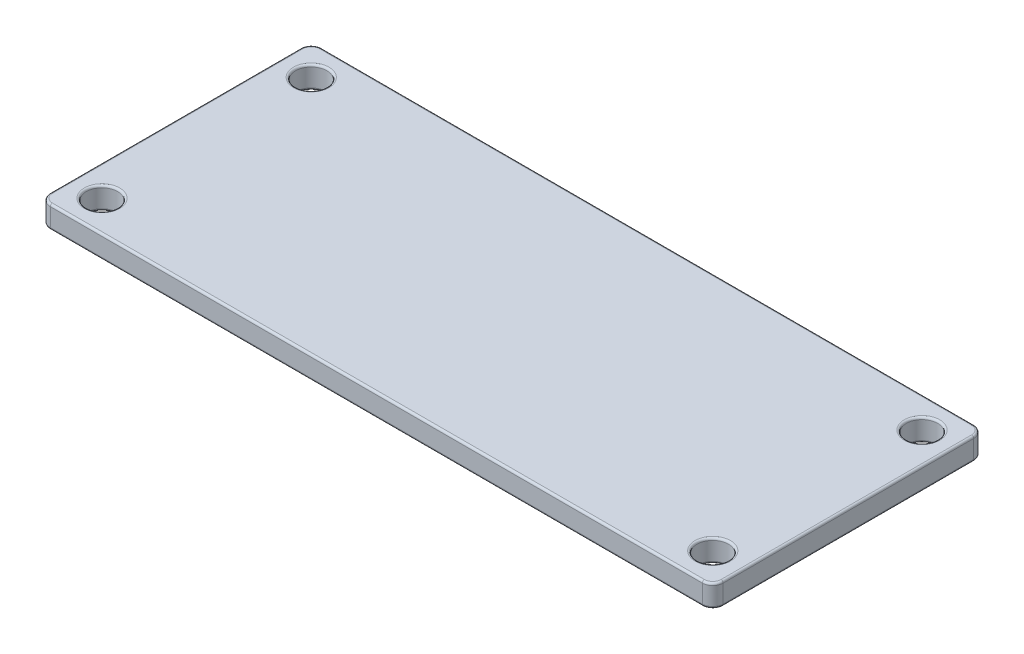
SolidWorks part; units mm, degrees
ref_plane "Front" through (0, 0, 0) normal (0, 0, 1) x (1, 0, 0)
ref_plane "Top" through (0, 0, 0) normal (0, 1, 0) x (1, 0, 0)
ref_plane "Right" through (0, 0, 0) normal (1, 0, 0) x (0, 0, -1)
sketch "Sketch1" plane through (0, 0, 0) normal (0, 1, 0) x (1, 0, 0)
  line L1 (-39.5006, 18.3467) -> (24.8634, 18.3467)
  line L2 (-39.5006, 18.3467) -> (-39.5006, -7.6123)
  line L3 (-39.5006, -7.6123) -> (24.8634, -7.6123)
  line L4 (24.8634, 18.3467) -> (24.8634, -7.6123)
  dimension "D1" = 64.364
  dimension "D2" = 25.959
extrude "Boss-Extrude1" add sketch "Sketch1" along normal blind 2.134
fillet "Fillet2" radius 1 4 edges at (-39.5006, 1.067, -18.3467) (-39.5006, 1.067, 7.6123) (24.8634, 1.067, -18.3467) (24.8634, 1.067, 7.6123)
sketch "Sketch2" plane through (0, 0, 0) normal (0, -1, 0) x (1, 0, 0)
  line L0 (24.8634, 6.6123) -> (24.8634, -17.3467) construction
  line L1 (-38.5006, 7.6123) -> (23.8634, 7.6123) construction
  line L2 (-39.5006, -17.3467) -> (-39.5006, 6.6123) construction
  line L3 (23.8634, -18.3467) -> (-38.5006, -18.3467) construction
  circle A0 centre (21.8914, 4.6403) radius 1.5
  circle A1 centre (21.8914, -15.3747) radius 1.5
  circle A2 centre (-36.5286, -15.3747) radius 1.5
  circle A3 centre (-36.5286, 4.6403) radius 1.5
  point P12 (0, 0)
  point P13 (0, 0)
  point P14 (0, 0)
  dimension "D1" = 3
  dimension "D2" = 3
  dimension "D3" = 3
  dimension "D4" = 3
  dimension "D5" = 2.972
  dimension "D6" = 2.972
  dimension "D7" = 2.972
  dimension "D8" = 2.972
  dimension "D9" = 2.972
  dimension "D10" = 2.972
  dimension "D11" = 2.972
  dimension "D12" = 2.972
extrude "Cut-Extrude1" cut sketch "Sketch2" against normal through all
fillet "Fillet3" radius 0.2 24 edges at (24.5705, 2.134, -18.0539) (24.8634, 2.134, -5.3672) (24.5705, 2.134, 7.3194) (-7.3186, 2.134, 7.6123) (-39.2078, 2.134, 7.3194) (-39.5006, 2.134, -5.3672) (-39.2078, 2.134, -18.0539) (-7.3186, 2.134, -18.3467) (21.8914, 2.134, 3.1403) (21.8914, 2.134, -16.8747) (-36.5286, 2.134, -16.8747) (-36.5286, 2.134, 3.1403) (-39.2078, 0, 7.3194) (-7.3186, 0, 7.6123) (24.5705, 0, 7.3194) (24.8634, 0, -5.3672) (24.5705, 0, -18.0539) (-7.3186, 0, -18.3467) (-39.2078, 0, -18.0539) (-39.5006, 0, -5.3672) (21.8914, 0, 3.1403) (21.8914, 0, -16.8747) (-36.5286, 0, -16.8747) (-36.5286, 0, 3.1403)
